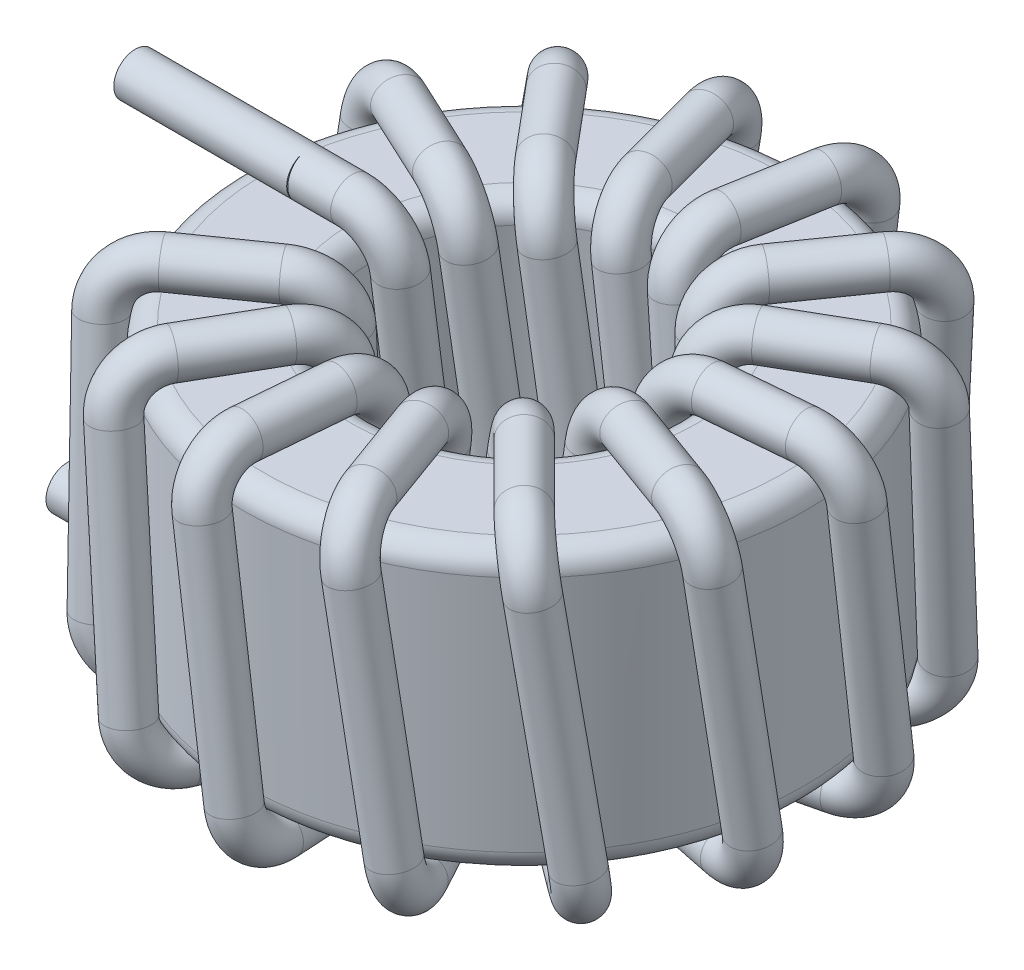
SolidWorks part; units mm, degrees
ref_plane "Alzado" through (0, 0, 0) normal (0, 0, 1) x (1, 0, 0)
ref_plane "Planta" through (0, 0, 0) normal (0, 1, 0) x (1, 0, 0)
ref_plane "Vista lateral" through (0, 0, 0) normal (1, 0, 0) x (0, 0, -1)
sketch "Croquis1" plane through (0, 0, 0) normal (0, 0, 1) x (1, 0, 0)
  line L0 (0, 0) -> (0, 6.6067) construction
  line L1 (-6, 3.25) -> (-4, 3.25)
  line L2 (-3.5, 2.75) -> (-3.5, -2.75)
  line L3 (-4, -3.25) -> (-6, -3.25)
  line L4 (-5, 3.25) -> (-5, -3.25) construction
  line L5 (-6.5, 2.75) -> (-6.5, -2.75)
  arc A0 (-3.5, -2.75) -> (-4, -3.25) centre (-4, -2.75) cw
  arc A1 (-3.5, 2.75) -> (-4, 3.25) centre (-4, 2.75) ccw
  arc A2 (-6.5, 2.75) -> (-6, 3.25) centre (-6, 2.75) cw
  arc A3 (-6.5, -2.75) -> (-6, -3.25) centre (-6, -2.75) ccw
  point P3 (-6, 16.0518)
  point P8 (-5, 3.25)
  point P11 (-49.8191, 25.344)
  point P12 (-50.3984, -24.7647)
  point P21 (-5, -3.25)
  point P22 (-6, -3.126)
  point P23 (-3.5, 0)
  point P24 (0, 15.1272)
  point P25 (-6, 13.6259)
  point P26 (-5, -7.142)
  point P27 (0, 6.6067)
  point P28 (-5, 3.25)
  point P29 (-5, -3.25)
  dimension "D1" = 6.5
  dimension "D2" = 5.5
  dimension "D3" = 3
  dimension "D4" = 6.5
revolve "Revolución1" add sketch "Croquis1" angle 360 about L0
ref_plane "Plano1" through (0, 3.75, 0) normal (0, 1, 0) x (1, 0, 0)
sketch "Croquis2" plane through (0, 3.75, 0) normal (0, 1, 0) x (1, 0, 0)
  line L0 (0, 0) -> (-7, 0)
  line L1 (0, 0) -> (-6.7064, 2.0059)
  line L2 (0, 0) -> (-5.8504, 3.8436)
  line L3 (0, 0) -> (-5.9708, 3.9227)
  line L4 (-6.3442, 2.9583) -> (0, 0) construction
  circle A0 centre (0, 0) radius 3
  circle A1 centre (-3, 0) radius 0.5
  circle A2 centre (0, 0) radius 7
  circle A4 centre (0, 0) radius 3.5 construction
  circle A5 centre (-5.8504, 3.8436) radius 0.5
  circle A6 centre (-2.8742, 0.8597) radius 0.5
  circle A7 centre (-6.7064, 2.0059) radius 0.5
  circle A8 centre (-6.9258, 1.0163) radius 0.5
  circle A9 centre (0, 0) radius 6.5 construction
  circle A11 centre (-3, 0) radius 0.8688 construction
  circle A13 centre (-2.5073, 1.6472) radius 0.5
  circle A14 centre (-2.8742, 0.8597) radius 0.8688 construction
  circle A15 centre (-6.3442, 2.9583) radius 0.5
  circle A16 centre (-5.8504, 3.8436) radius 1.0136 construction
  circle A17 centre (-6.7064, 2.0059) radius 1.0136 construction
  circle A18 centre (-2.7189, 1.2679) radius 0.5
  point P30 (-2.7276, 1.2491)
  point P31 (0, 0)
  dimension "D1" = 1
  dimension "D2" = 25
ref_plane "Plano2" through (0, -3.75, 0) normal (0, -1, 0) x (-1, 0, 0)
sketch "Croquis3" plane through (0, -3.75, 0) normal (0, -1, 0) x (1, 0, 0)
  circle A1 centre (-3, 0) radius 0.5 construction
  circle A3 centre (-3, 0) radius 0.5
  circle A6 centre (-2.5073, -1.6472) radius 0.5 construction
  circle A7 centre (-2.5073, -1.6472) radius 0.5
  circle A8 centre (-6.3442, -2.9583) radius 0.5 construction
  circle A9 centre (-6.3442, -2.9583) radius 0.5
  circle A10 centre (-2.8742, -0.8597) radius 0.5 construction
  circle A11 centre (-2.8742, -0.8597) radius 0.5
  circle A12 centre (-5.8504, -3.8436) radius 0.5 construction
  circle A13 centre (-6.7064, -2.0059) radius 0.5 construction
  circle A14 centre (-5.8504, -3.8436) radius 0.5
  circle A15 centre (-6.7064, -2.0059) radius 0.5
  circle A16 centre (-6.9258, -1.0163) radius 0.5 construction
  circle A17 centre (-6.9258, -1.0163) radius 0.5
sketch3d "Croquis3D1"
  line L0 (4, 3.25, 0) -> (0, 3.25, 0) construction
  line L1 (4, 3.25, 0) -> (6, 3.25, 0) construction
  line L2 (5, 3.75, 0) -> (5, 3.25, 0) construction
  line L3 (-6.3442, 3.75, -2.9583) -> (-4.5315, 3.75, -2.1131) construction
  line L4 (-5, 3.75, 0) -> (-3.9835, 3.75, 0)
  line L5 (-6.3442, 3.75, -2.9583) -> (-6.7064, -3.75, -2.0059) construction
  line L7 (0, 3.75, 0) -> (-7, 3.75, 0) construction
  line L8 (-2.9836, 2.7731, -0.112) -> (-2.8906, -2.7731, -0.7477)
  line L9 (-3.8164, -3.75, -1.1415) -> (-5.7389, -3.75, -1.7165)
  line L10 (-6.6581, -2.7493, -2.133) -> (-6.3925, 2.7493, -2.8313)
  line L11 (-5.4289, 3.75, -2.5315) -> (-4.5315, 3.75, -2.1131)
  line L12 (-6.3442, 3.75, -2.9583) -> (0, 3.75, 0) construction
  circle A4 centre (0, 3.75, 0) radius 5 construction
  circle A5 centre (0, 3.25, 0) radius 4 construction
  circle A7 centre (0, 3.25, 0) radius 4 construction
  circle A8 centre (0, 3.25, 0) radius 6 construction
  circle A9 centre (0, 3.25, 0) radius 6 construction
  arc A10 (-5.7389, -3.75, -1.7165) -> (-6.6581, -2.7493, -2.133) centre (-5.7005, -2.7591, -1.8452) ccw
  arc A11 (-2.8906, -2.7731, -0.7477) -> (-3.8164, -3.75, -1.1415) centre (-3.8491, -2.7565, -1.0324) ccw
  arc A12 (-3.9835, 3.75, 0) -> (-2.9836, 2.7731, -0.112) centre (-3.9835, 2.7565, -0.1139) ccw
  arc A13 (-6.3925, 2.7493, -2.8313) -> (-5.4289, 3.75, -2.5315) centre (-5.4857, 2.7591, -2.4098) ccw
  point P2 (0, -1.25, 0)
  point P5 (0, -0.75, 0)
  point P7 (0, -0.75, 0)
  point P10 (0, -2.75, 0)
  point P12 (0, -2.75, 0)
  point P29 (-6.7064, -3.75, -2.0059)
  point P30 (-5.4165, -2.8933, -2.7946)
  point P33 (-2.8742, -3.75, -0.8597)
  point P34 (-3.5644, -2.6426, -1.9842)
  point P37 (-3, 3.75, 0)
  point P38 (-3.9835, 2.8704, -1.1074)
  point P45 (-6.3442, 3.75, -2.9583)
  point P53 (-5.0669, 2.6248, -3.3079)
  dimension "D1" = 1
sweep "Barrer3" add path "Croquis3D1" circular profile diameter 0.99 parameters "D3"=0.99
pattern_circular "MatrizC1" count 14 every 25 about axis through (0, 0, 0) along (0, -1, 0) of "Barrer3"
ref_plane "Plano3" through (-5, 0, 0) normal (-1, 0, 0) x (0, 0, 1)
sketch "Croquis172" plane through (0, 0, 0) normal (0, 0, 1) x (1, 0, 0)
  line L0 (-5, 5.223) -> (-5, 3.25)
  line L1 (-5, 0.5445) -> (-5, -0.5445) construction
  line L2 (-5, 5.223) -> (-8.7456, 5.223)
  line L3 (-6, 3.25) -> (-5, 3.25)
  line L4 (-6.5, 2.75) -> (-6.5, -2.75)
  line L5 (-6, -3.25) -> (-4, -3.25)
  line L6 (-8.7456, 5.223) -> (-8.7456, -4.9771)
  line L7 (-8.7456, -4.9771) -> (-5, -4.9771)
  line L8 (-5, -3.25) -> (-5, -4.9771)
  line L9 (0, 0) -> (0, 9.5394) construction
  arc A0 (-6, 3.25) -> (-6.5, 2.75) centre (-6, 2.75) ccw construction
  arc A1 (-6, 3.25) -> (-6.5, 2.75) centre (-6, 2.75) ccw
  arc A2 (-6.5, -2.75) -> (-6, -3.25) centre (-6, -2.75) ccw construction
  arc A3 (-6.5, -2.75) -> (-6, -3.25) centre (-6, -2.75) ccw
revolve "Cortar-Revolución1" cut sketch "Croquis172" angle 24 about L9
sketch "Croquis173" plane through (-5, 0, 0) normal (-1, 0, 0) x (0, 0, 1)
  line L0 (0, 4.245) -> (0, 3.255) construction
  circle A4 centre (1.5675, -3.7416) radius 0.495
  circle A5 centre (0, 3.75) radius 0.495
extrude "Saliente-Extruir1" add sketch "Croquis173" along normal blind 4
